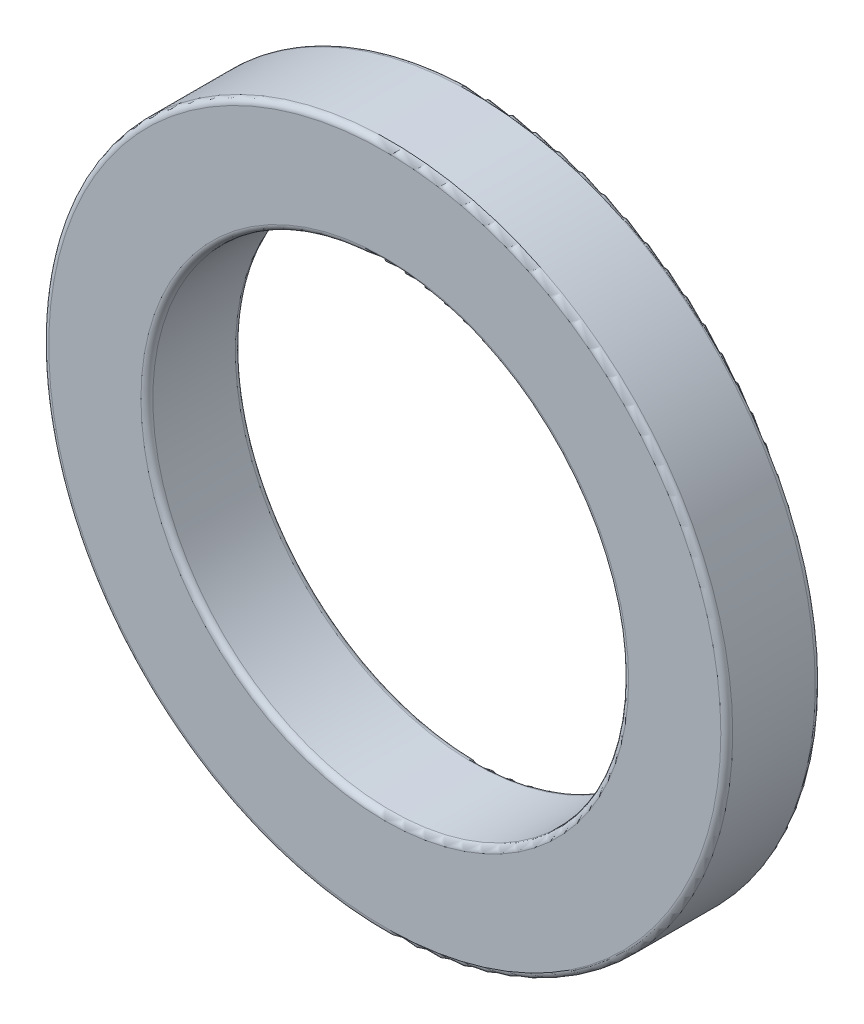
SolidWorks part; units mm, degrees
material "Plain Carbon Steel"
ref_plane "Front Plane" through (0, 0, 0) normal (0, 0, 1) x (1, 0, 0)
ref_plane "Top Plane" through (0, 0, 0) normal (0, 1, 0) x (1, 0, 0)
ref_plane "Right Plane" through (0, 0, 0) normal (1, 0, 0) x (0, 0, -1)
sketch "Sketch1" plane through (0, 0, 0) normal (0, 0, 1) x (1, 0, 0)
  circle A0 centre (0, 0) radius 4
  circle A1 centre (0, 0) radius 5.75
  dimension "D2" = 8
  dimension "D1" = 1.75
extrude "Boss-Extrude1" add sketch "Sketch1" along normal mid plane 1.5875
fillet "Fillet1" radius 0.1 4 edges at (5.75, 0, -0.7937) (5.75, 0, 0.7937) (4, 0, -0.7937) (4, 0, 0.7937)
